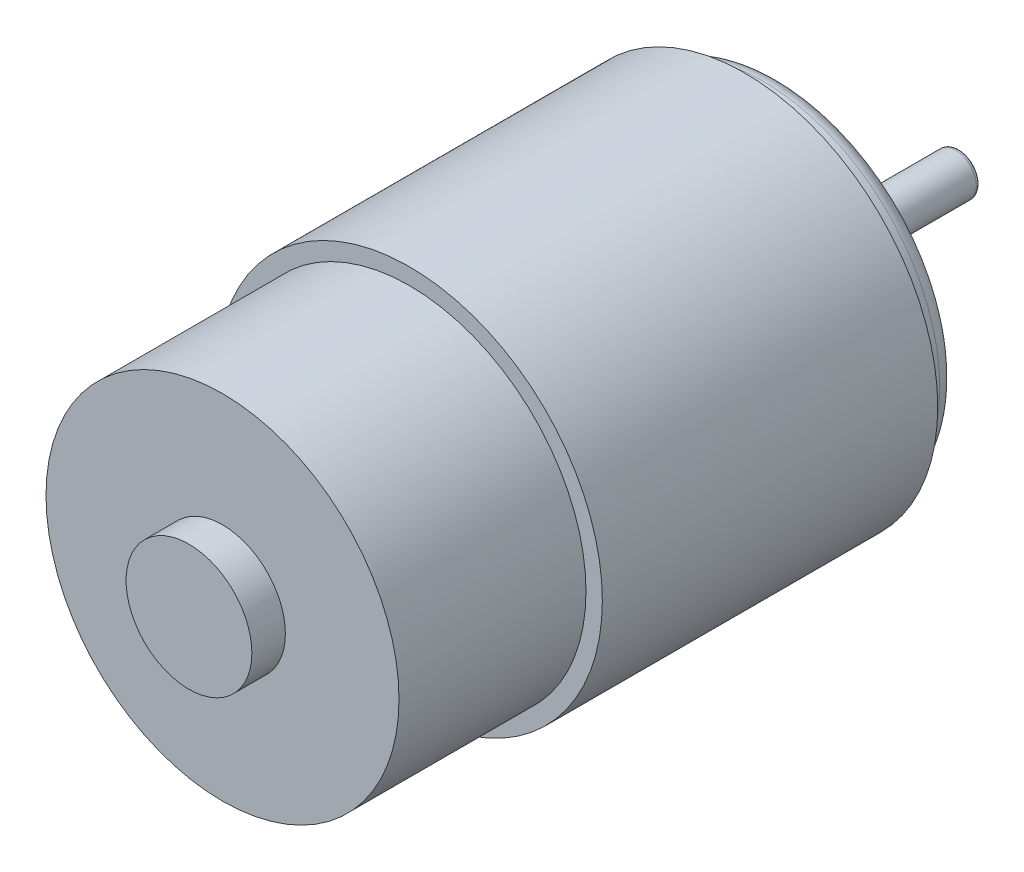
SolidWorks part; units mm, degrees
ref_plane "Front Plane" through (0, 0, 0) normal (0, 0, 1) x (1, 0, 0)
ref_plane "Top Plane" through (0, 0, 0) normal (0, 1, 0) x (1, 0, 0)
ref_plane "Right Plane" through (0, 0, 0) normal (1, 0, 0) x (0, 0, -1)
sketch "Sketch1" plane through (0, 0, 0) normal (0, 0, 1) x (1, 0, 0)
  circle A0 centre (0, 0) radius 23
  dimension "D1" = 46
extrude "Boss-Extrude1" add sketch "Sketch1" along normal blind 40
sketch "Sketch2" plane through (0, 0, 40) normal (0, 0, 1) x (1, 0, 0)
  circle A0 centre (0, 0) radius 21.05
  dimension "D1" = 42.1
extrude "Boss-Extrude2" add sketch "Sketch2" along normal blind 22.3
sketch "Sketch3" plane through (0, 0, 0) normal (0, 0, -1) x (-1, 0, 0)
  circle A0 centre (0, 0) radius 21.05
  dimension "D1" = 42.1
extrude "Boss-Extrude3" add sketch "Sketch3" along normal blind 4.2
fillet "Fillet1" radius 2 1 edges at (-21.05, 0, -4.2)
sketch "Sketch4" plane through (0, 0, -4.2) normal (0, 0, -1) x (-1, 0, 0)
  circle A0 centre (0, 0) radius 7.5
  dimension "D1" = 15
extrude "Boss-Extrude4" add sketch "Sketch4" along normal blind 4.4
fillet "Fillet2" radius 2 1 edges at (-7.5, 0, -8.6)
sketch "Sketch5" plane through (0, 0, -8.6) normal (0, 0, -1) x (-1, 0, 0)
  circle A0 centre (0, 0) radius 2.5
  dimension "D1" = 5
extrude "Boss-Extrude5" add sketch "Sketch5" along normal blind 17
fillet "Fillet3" radius 0.5 1 edges at (-2.5, 0, -25.6)
sketch "Sketch6" plane through (0, 0, 62.3) normal (0, 0, 1) x (1, 0, 0)
  circle A0 centre (0, 0) radius 7.5
  dimension "D1" = 15
extrude "Boss-Extrude6" add sketch "Sketch6" along normal blind 4
sketch "Sketch7" plane through (0, 0, -4.2) normal (0, 0, -1) x (-1, 0, 0)
  circle A0 centre (0, 14.5) radius 2.25
  circle A1 centre (14.5, 0) radius 2.25
  circle A2 centre (0, -14.5) radius 2.25
  circle A3 centre (-14.5, 0) radius 2.25
  point P8 (0, 0)
  dimension "D1" = 4.5
  dimension "D2" = 4.5
  dimension "D3" = 4.5
  dimension "D4" = 4.5
extrude "Cut-Extrude1" cut sketch "Sketch7" against normal blind 0.7
